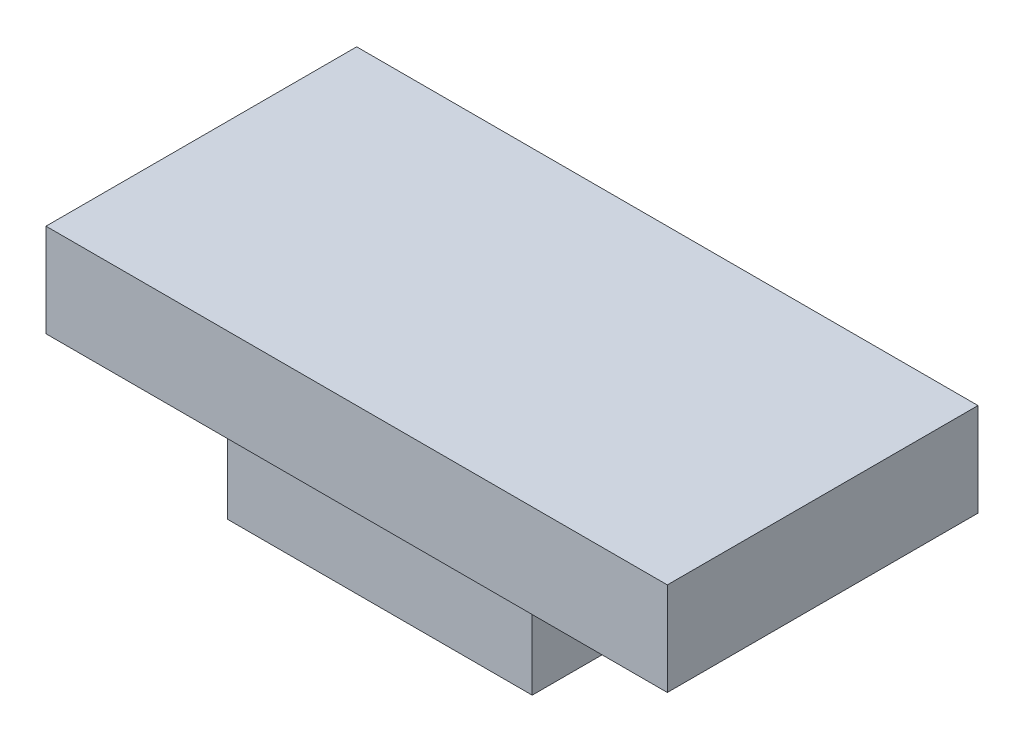
SolidWorks part; units mm, degrees
ref_plane "Front Plane" through (0, 0, 0) normal (0, 0, 1) x (1, 0, 0)
ref_plane "Top Plane" through (0, 0, 0) normal (0, 1, 0) x (1, 0, 0)
ref_plane "Right Plane" through (0, 0, 0) normal (1, 0, 0) x (0, 0, -1)
sketch "Sketch1" plane through (0, 0, 0) normal (0, 1, 0) x (1, 0, 0)
  line L1 (-10, -5) -> (10, -5)
  line L2 (-10, -5) -> (-10, 5)
  line L3 (-10, 5) -> (10, 5)
  line L4 (10, -5) -> (10, 5)
  line L5 (-10, -5) -> (10, 5) construction
  line L6 (-10, 5) -> (10, -5) construction
  point P0 (0, 0)
  dimension "D1" = 20
  dimension "D2" = 10
extrude "Boss-Extrude1" add sketch "Sketch1" along normal blind 3
sketch "Sketch2" plane through (0, 0, 0) normal (0, -1, 0) x (1, 0, 0)
  line L1 (-2.9, -2.25) -> (2.9, -2.25)
  line L2 (-2.9, -2.25) -> (-2.9, 2.25)
  line L3 (-2.9, 2.25) -> (2.9, 2.25)
  line L4 (2.9, -2.25) -> (2.9, 2.25)
  line L5 (-2.9, -2.25) -> (2.9, 2.25) construction
  line L6 (-2.9, 2.25) -> (2.9, -2.25) construction
  line L7 (-4.9, -4.25) -> (4.9, -4.25)
  line L8 (-4.9, -4.25) -> (-4.9, 4.25)
  line L9 (-4.9, 4.25) -> (4.9, 4.25)
  line L10 (4.9, -4.25) -> (4.9, 4.25)
  line L11 (-4.9, -4.25) -> (4.9, 4.25) construction
  line L12 (-4.9, 4.25) -> (4.9, -4.25) construction
  point P0 (0, 0)
  point P6 (0, 0)
  dimension "D1" = 4.5
  dimension "D2" = 5.8
  dimension "D3" = 2
  dimension "D4" = 2
extrude "Boss-Extrude2" add sketch "Sketch2" along normal blind 3
